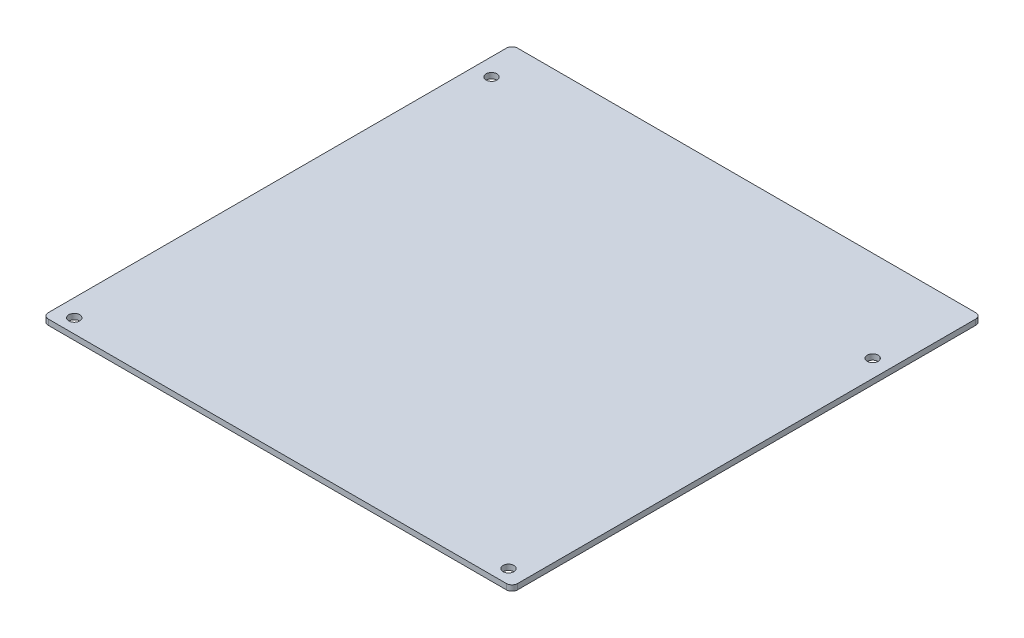
SolidWorks part; units mm, degrees
ref_plane "Front Plane" through (0, 0, 0) normal (0, 0, 1) x (1, 0, 0)
ref_plane "Top Plane" through (0, 0, 0) normal (0, 1, 0) x (1, 0, 0)
ref_plane "Right Plane" through (0, 0, 0) normal (1, 0, 0) x (0, 0, -1)
sketch "Sketch1" plane through (0, 0, 0) normal (0, 1, 0) x (1, 0, 0)
  line L1 (-85.09, -85.09) -> (85.09, -85.09)
  line L2 (-85.09, -85.09) -> (-85.09, 85.09)
  line L3 (-85.09, 85.09) -> (85.09, 85.09)
  line L4 (85.09, -85.09) -> (85.09, 85.09)
  line L5 (-85.09, -85.09) -> (85.09, 85.09) construction
  line L6 (-85.09, 85.09) -> (85.09, -85.09) construction
  point P0 (0, 0)
  dimension "D1" = 170.18
  dimension "D2" = 170.18
extrude "Boss-Extrude1" add sketch "Sketch1" along normal blind 2
fillet "Fillet1" radius 2 4 edges at (-85.09, 1, -85.09) (85.09, 1, -85.09) (85.09, 1, 85.09) (-85.09, 1, 85.09)
sketch "Sketch2" plane through (0, 0, 0) normal (0, 1, 0) x (1, 0, 0)
  line L0 (-85.09, 83.09) -> (-85.09, -83.09) construction
  line L1 (-83.09, -85.09) -> (83.09, -85.09) construction
  point P0 (-78.74, -80.01)
  point P1 (78.74, -80.01)
  point P2 (78.74, 52.07)
  point P3 (-78.74, 71.3216)
  point P6 (0, 0)
  point P9 (0, 0)
  point P10 (0, 0)
  point P11 (0, 0)
  point P12 (-78.74, 71.3216)
  dimension "D1" = 6.35
  dimension "D2" = 5.08
  dimension "D3" = 157.48
  dimension "D4" = 132.08
sketch "Sketch3" plane through (0, 2, 0) normal (0, 1, 0) x (1, 0, 0)
  circle A0 centre (-78.74, 71.3216) radius 1.975
  circle A1 centre (78.74, 52.07) radius 1.975
  circle A2 centre (78.74, -80.01) radius 1.975
  circle A3 centre (-78.74, -80.01) radius 1.975
  dimension "D1" = 3.95
extrude "Cut-Extrude1" cut sketch "Sketch3" against normal through all
